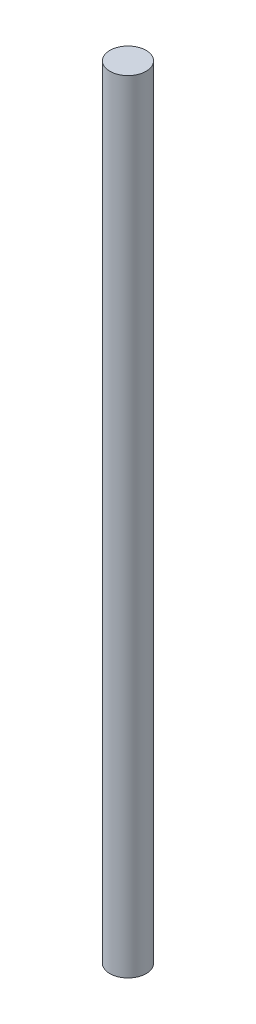
SolidWorks part; units mm, degrees
ref_plane "Alzado" through (0, 0, 0) normal (0, 0, 1) x (1, 0, 0)
ref_plane "Planta" through (0, 0, 0) normal (0, 1, 0) x (1, 0, 0)
ref_plane "Vista lateral" through (0, 0, 0) normal (1, 0, 0) x (0, 0, -1)
sketch "Croquis1" plane through (0, 0, 0) normal (0, 1, 0) x (1, 0, 0)
  circle A0 centre (0, 0) radius 1.925
  dimension "D1" = 3.85
extrude "Saliente-Extruir1" add sketch "Croquis1" along normal blind 83
